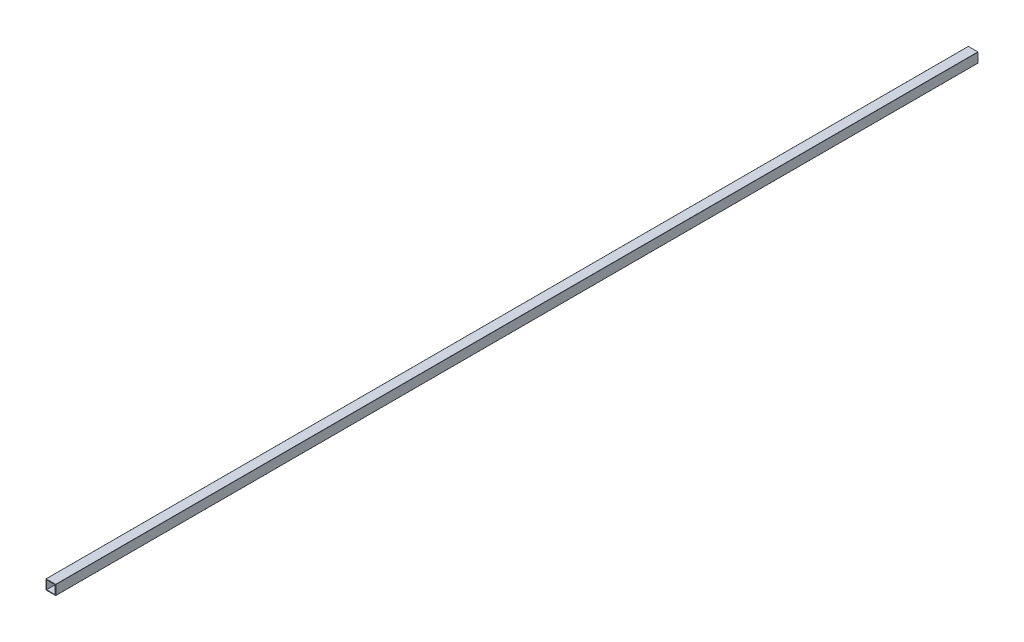
SolidWorks part; units mm, degrees
material "AISI 1035 Acero (SS)"
ref_plane "Alzado" through (0, 0, 0) normal (0, 0, 1) x (1, 0, 0)
ref_plane "Planta" through (0, 0, 0) normal (0, 1, 0) x (1, 0, 0)
ref_plane "Vista lateral" through (0, 0, 0) normal (1, 0, 0) x (0, 0, -1)
sketch "Croquis1" plane through (0, 0, 0) normal (0, 0, 1) x (1, 0, 0)
  line L0 (-27.95, -27.95) -> (-27.95, 27.95)
  line L1 (-30.75, -31.75) -> (30.75, -31.75)
  line L2 (-31.75, -30.75) -> (-31.75, 30.75)
  line L3 (-30.75, 31.75) -> (30.75, 31.75)
  line L4 (31.75, -30.75) -> (31.75, 30.75)
  line L5 (-31.75, -31.75) -> (31.75, 31.75) construction
  line L6 (-31.75, 31.75) -> (31.75, -31.75) construction
  line L7 (-27.95, 27.95) -> (27.95, 27.95)
  line L8 (27.95, -27.95) -> (27.95, 27.95)
  line L9 (-27.95, -27.95) -> (27.95, -27.95)
  line L10 (-31.75, 31.75) -> (31.75, 31.75) construction
  line L11 (31.75, -31.75) -> (31.75, 31.75) construction
  line L12 (-31.75, -31.75) -> (31.75, -31.75) construction
  line L13 (-31.75, -31.75) -> (-31.75, 31.75) construction
  arc A0 (30.75, 31.75) -> (31.75, 30.75) centre (30.75, 30.75) cw
  arc A1 (30.75, -31.75) -> (31.75, -30.75) centre (30.75, -30.75) ccw
  arc A2 (-30.75, -31.75) -> (-31.75, -30.75) centre (-30.75, -30.75) cw
  arc A3 (-31.75, 30.75) -> (-30.75, 31.75) centre (-30.75, 30.75) cw
  point P0 (0, 0)
  dimension "D2" = 1
  dimension "D1" = 63.5
  dimension "D3" = 3.8
extrude "Saliente-Extruir1" add sketch "Croquis1" along normal blind 6000
